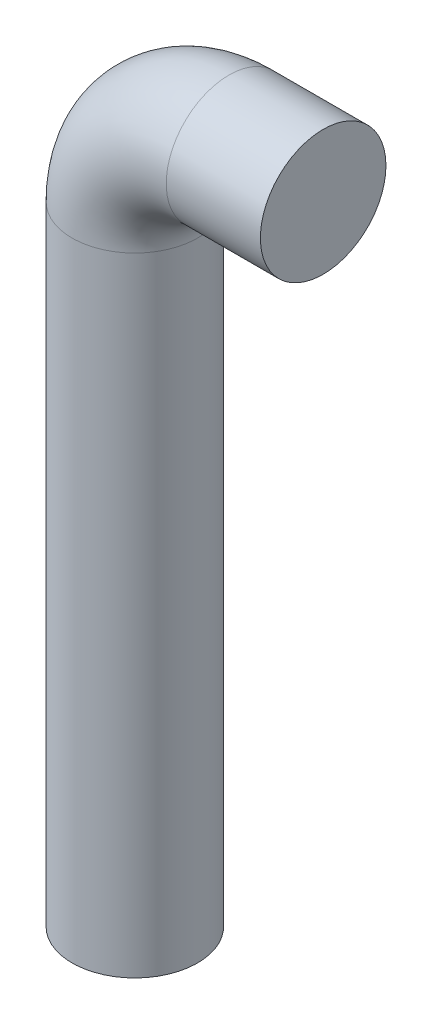
SolidWorks part; units mm, degrees
ref_plane "Front Plane" through (0, 0, 0) normal (0, 0, 1) x (1, 0, 0)
ref_plane "Top Plane" through (0, 0, 0) normal (0, 1, 0) x (1, 0, 0)
ref_plane "Right Plane" through (0, 0, 0) normal (1, 0, 0) x (0, 0, -1)
sketch "Sketch1" plane through (0, 0, 0) normal (0, 0, 1) x (1, 0, 0)
  line L0 (0, 0) -> (-3, 0)
  line L1 (-6, -3) -> (-6, -23)
  arc A0 (-6, -3) -> (-3, 0) centre (-3, -3) cw
  dimension "D3" = 3
  dimension "D2" = 3
  dimension "D1" = 20
sketch "Sketch2" plane through (0, 0, 0) normal (1, 0, 0) x (0, 0, -1)
  circle A0 centre (0, 0) radius 2
  dimension "D1" = 4
sweep "Sweep1" add profiles "Sketch2" path "Sketch1"
